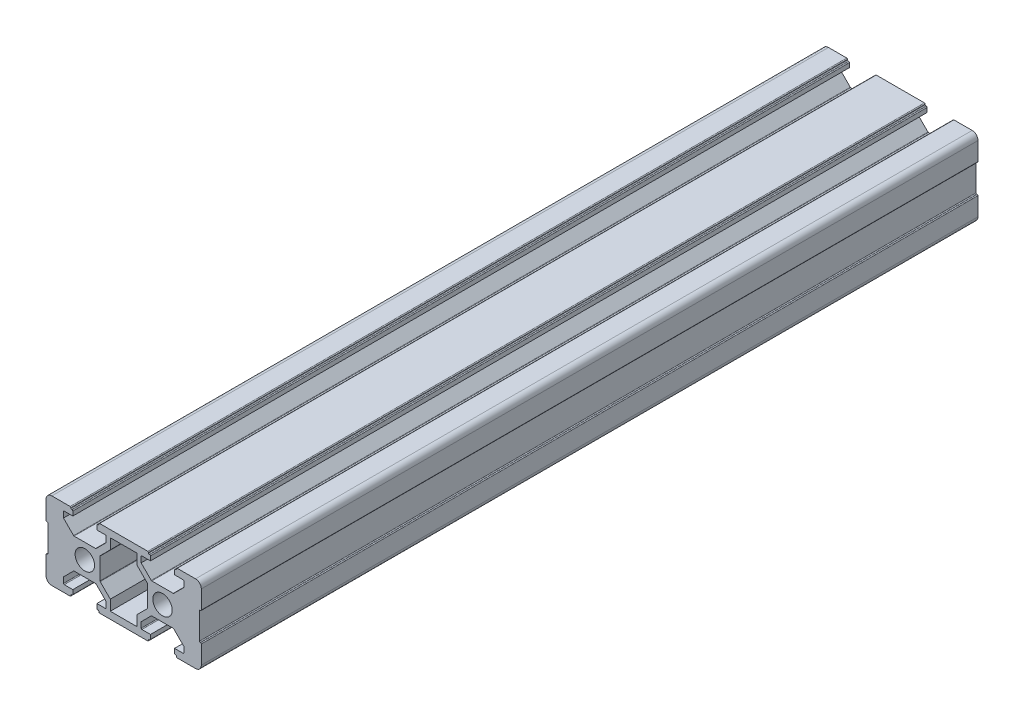
SolidWorks part; units mm, degrees
ref_plane "前视基准面" through (0, 0, 0) normal (0, 0, 1) x (1, 0, 0)
ref_plane "上视基准面" through (0, 0, 0) normal (0, 1, 0) x (1, 0, 0)
ref_plane "右视基准面" through (0, 0, 0) normal (1, 0, 0) x (0, 0, -1)
sketch "Sketch1" plane through (0, 0, 0) normal (0, 0, 1) x (1, 0, 0)
  line L0 (-8.5, 10) -> (-3.8, 10)
  line L3 (-8.5, -10) -> (-3.8, -10)
  line L5 (-10, 8.5) -> (-10, 3.8)
  line L6 (-2.7565, 3.9) -> (2.7565, 3.9)
  line L9 (-2.7565, -3.9) -> (2.7565, -3.9)
  line L10 (3.9, 2.7565) -> (3.9, -2.7565)
  line L13 (3.6, 9.7) -> (3.6, 9.8)
  line L14 (3.1, -8.2) -> (5.3, -8.2)
  line L15 (-2.8979, -3.9586) -> (-5.5, -6.5607)
  line L16 (-3.1, -8.2) -> (-3.1, -9.3)
  line L17 (3.1, -8.2) -> (3.1, -9.3)
  line L18 (-5.5, -6.5607) -> (-5.5, -8)
  line L19 (5.5, -6.5607) -> (5.5, -8)
  line L20 (-5.3, -8.2) -> (-3.1, -8.2)
  line L21 (-3.4, -9.5) -> (-3.3, -9.5)
  line L22 (3.8, -10) -> (8.5, -10)
  line L23 (3.3, -9.5) -> (3.4, -9.5)
  line L24 (-3.6, -9.7) -> (-3.6, -9.8)
  line L25 (3.6, -9.7) -> (3.6, -9.8)
  line L27 (-9.7, -3.6) -> (-9.8, -3.6)
  line L28 (-9.5, -3.4) -> (-9.5, -3.3)
  line L31 (-10, -3.8) -> (-10, -8.5)
  line L33 (3.8, 10) -> (8.5, 10)
  line L34 (2.8979, -3.9586) -> (5.5, -6.5607)
  line L40 (3.9586, -2.8979) -> (6.5607, -5.5)
  line L41 (3.3, 9.5) -> (3.4, 9.5)
  line L42 (30, 8.5) -> (30, 3.8)
  line L43 (3.1, 8.2) -> (3.1, 9.3)
  line L44 (3.1, 8.2) -> (5.3, 8.2)
  line L45 (5.5, 6.5607) -> (5.5, 8)
  line L46 (2.8979, 3.9586) -> (5.5, 6.5607)
  line L52 (3.9586, 2.8979) -> (6.5607, 5.5)
  line L53 (-3.6, 9.7) -> (-3.6, 9.8)
  line L54 (-3.4, 9.5) -> (-3.3, 9.5)
  line L55 (-3.1, 8.2) -> (-3.1, 9.3)
  line L56 (-5.3, 8.2) -> (-3.1, 8.2)
  line L57 (-5.5, 6.5607) -> (-5.5, 8)
  line L58 (-2.8979, 3.9586) -> (-5.5, 6.5607)
  line L59 (-9.5, 3.4) -> (-9.5, 3.3)
  line L60 (-9.7, 3.6) -> (-9.8, 3.6)
  line L65 (29.7, 3.6) -> (29.8, 3.6)
  line L66 (29.5, 3.4) -> (29.5, 3.3)
  line L76 (29.5, -3.4) -> (29.5, -3.3)
  line L77 (29.7, -3.6) -> (29.8, -3.6)
  line L78 (30, -3.8) -> (30, -8.5)
  line L79 (28.5, -10) -> (23.8, -10)
  line L80 (23.6, -9.7) -> (23.6, -9.8)
  line L81 (23.4, -9.5) -> (23.3, -9.5)
  line L82 (23.1, -8.2) -> (23.1, -9.3)
  line L83 (25.3, -8.2) -> (23.1, -8.2)
  line L84 (25.5, -6.5607) -> (25.5, -8)
  line L85 (22.8979, -3.9586) -> (25.5, -6.5607)
  line L86 (22.7565, -3.9) -> (17.2435, -3.9)
  line L87 (17.1021, -3.9586) -> (14.5, -6.5607)
  line L88 (14.5, -6.5607) -> (14.5, -8)
  line L89 (16.9, -8.2) -> (14.7, -8.2)
  line L90 (16.9, -8.2) -> (16.9, -9.3)
  line L91 (16.7, -9.5) -> (16.6, -9.5)
  line L92 (16.4, -9.7) -> (16.4, -9.8)
  line L93 (16.2, -10) -> (11.5, -10)
  line L94 (13.4393, 5.5) -> (13.4393, 8.2)
  line L96 (6.5607, 5.5) -> (6.5607, 8.2)
  line L97 (6.5607, 8.2) -> (13.4393, 8.2)
  line L99 (16.0414, -2.8979) -> (13.4393, -5.5)
  line L100 (16.1, 2.7565) -> (16.1, -2.7565)
  line L101 (16.0414, 2.8979) -> (13.4393, 5.5)
  line L107 (16.2, 10) -> (11.5, 10)
  line L108 (16.4, 9.7) -> (16.4, 9.8)
  line L109 (16.7, 9.5) -> (16.6, 9.5)
  line L110 (16.9, 8.2) -> (16.9, 9.3)
  line L111 (16.9, 8.2) -> (14.7, 8.2)
  line L112 (14.5, 6.5607) -> (14.5, 8)
  line L113 (17.1021, 3.9586) -> (14.5, 6.5607)
  line L114 (22.7565, 3.9) -> (17.2435, 3.9)
  line L115 (22.8979, 3.9586) -> (25.5, 6.5607)
  line L116 (25.5, 6.5607) -> (25.5, 8)
  line L117 (25.3, 8.2) -> (23.1, 8.2)
  line L118 (23.1, 8.2) -> (23.1, 9.3)
  line L119 (23.4, 9.5) -> (23.3, 9.5)
  line L120 (23.6, 9.7) -> (23.6, 9.8)
  line L121 (28.5, 10) -> (23.8, 10)
  line L122 (13.4393, -5.5) -> (13.4393, -8.2)
  line L124 (6.5607, -5.5) -> (6.5607, -8.2)
  line L125 (6.5607, -8.2) -> (13.4393, -8.2)
  line L127 (8.5, 10) -> (11.5, 10)
  line L128 (8.5, -10) -> (11.5, -10)
  line L129 (-9.5, -3.3) -> (-9.5, 3.3)
  line L130 (29.5, -3.3) -> (29.5, 3.3)
  arc A3 (-8.5, -10) -> (-10, -8.5) centre (-8.5, -8.5) cw
  arc A4 (-10, 8.5) -> (-8.5, 10) centre (-8.5, 8.5) cw
  arc A5 (3.4, -9.5) -> (3.6, -9.7) centre (3.4, -9.7) cw
  arc A6 (3.8, -10) -> (3.6, -9.8) centre (3.8, -9.8) cw
  arc A7 (3.3, -9.5) -> (3.1, -9.3) centre (3.3, -9.3) cw
  arc A8 (5.3, -8.2) -> (5.5, -8) centre (5.3, -8) ccw
  arc A11 (-2.7565, 3.9) -> (-2.8979, 3.9586) centre (-2.7565, 4.1) cw
  arc A12 (2.7565, 3.9) -> (2.8979, 3.9586) centre (2.7565, 4.1) ccw
  arc A13 (3.9586, 2.8979) -> (3.9, 2.7565) centre (4.1, 2.7565) ccw
  arc A14 (3.9, -2.7565) -> (3.9586, -2.8979) centre (4.1, -2.7565) ccw
  arc A15 (-2.8979, -3.9586) -> (-2.7565, -3.9) centre (-2.7565, -4.1) cw
  arc A16 (2.7565, -3.9) -> (2.8979, -3.9586) centre (2.7565, -4.1) cw
  arc A17 (-3.6, -9.8) -> (-3.8, -10) centre (-3.8, -9.8) cw
  arc A18 (-3.3, -9.5) -> (-3.1, -9.3) centre (-3.3, -9.3) ccw
  arc A19 (-3.6, -9.7) -> (-3.4, -9.5) centre (-3.4, -9.7) cw
  arc A24 (-5.3, -8.2) -> (-5.5, -8) centre (-5.3, -8) cw
  arc A31 (3.1, 9.3) -> (3.3, 9.5) centre (3.3, 9.3) cw
  arc A32 (3.6, 9.8) -> (3.8, 10) centre (3.8, 9.8) cw
  arc A33 (3.6, 9.7) -> (3.4, 9.5) centre (3.4, 9.7) cw
  arc A34 (-3.8, 10) -> (-3.6, 9.8) centre (-3.8, 9.8) cw
  arc A35 (-3.3, 9.5) -> (-3.1, 9.3) centre (-3.3, 9.3) cw
  arc A36 (-3.4, 9.5) -> (-3.6, 9.7) centre (-3.4, 9.7) cw
  arc A37 (5.5, 8) -> (5.3, 8.2) centre (5.3, 8) ccw
  arc A38 (-5.5, 8) -> (-5.3, 8.2) centre (-5.3, 8) cw
  arc A39 (-10, 3.8) -> (-9.8, 3.6) centre (-9.8, 3.8) ccw
  arc A41 (-9.7, 3.6) -> (-9.5, 3.4) centre (-9.7, 3.4) cw
  arc A42 (-10, -3.8) -> (-9.8, -3.6) centre (-9.8, -3.8) cw
  arc A44 (-9.5, -3.4) -> (-9.7, -3.6) centre (-9.7, -3.4) cw
  arc A45 (30, 8.5) -> (28.5, 10) centre (28.5, 8.5) ccw
  arc A46 (30, 3.8) -> (29.8, 3.6) centre (29.8, 3.8) cw
  arc A47 (29.7, 3.6) -> (29.5, 3.4) centre (29.7, 3.4) ccw
  arc A54 (29.5, -3.4) -> (29.7, -3.6) centre (29.7, -3.4) ccw
  arc A55 (30, -3.8) -> (29.8, -3.6) centre (29.8, -3.8) ccw
  arc A56 (28.5, -10) -> (30, -8.5) centre (28.5, -8.5) ccw
  arc A57 (23.6, -9.8) -> (23.8, -10) centre (23.8, -9.8) ccw
  arc A58 (23.6, -9.7) -> (23.4, -9.5) centre (23.4, -9.7) ccw
  arc A59 (23.3, -9.5) -> (23.1, -9.3) centre (23.3, -9.3) cw
  arc A60 (25.3, -8.2) -> (25.5, -8) centre (25.3, -8) ccw
  arc A61 (22.8979, -3.9586) -> (22.7565, -3.9) centre (22.7565, -4.1) ccw
  arc A62 (17.2435, -3.9) -> (17.1021, -3.9586) centre (17.2435, -4.1) ccw
  arc A63 (14.7, -8.2) -> (14.5, -8) centre (14.7, -8) cw
  arc A64 (16.7, -9.5) -> (16.9, -9.3) centre (16.7, -9.3) ccw
  arc A65 (16.6, -9.5) -> (16.4, -9.7) centre (16.6, -9.7) ccw
  arc A66 (16.2, -10) -> (16.4, -9.8) centre (16.2, -9.8) ccw
  arc A72 (16.1, -2.7565) -> (16.0414, -2.8979) centre (15.9, -2.7565) cw
  arc A73 (16.0414, 2.8979) -> (16.1, 2.7565) centre (15.9, 2.7565) cw
  arc A79 (16.4, 9.8) -> (16.2, 10) centre (16.2, 9.8) ccw
  arc A80 (16.4, 9.7) -> (16.6, 9.5) centre (16.6, 9.7) ccw
  arc A81 (16.9, 9.3) -> (16.7, 9.5) centre (16.7, 9.3) ccw
  arc A82 (14.5, 8) -> (14.7, 8.2) centre (14.7, 8) cw
  arc A83 (17.2435, 3.9) -> (17.1021, 3.9586) centre (17.2435, 4.1) cw
  arc A84 (22.7565, 3.9) -> (22.8979, 3.9586) centre (22.7565, 4.1) ccw
  arc A85 (25.5, 8) -> (25.3, 8.2) centre (25.3, 8) ccw
  arc A86 (23.3, 9.5) -> (23.1, 9.3) centre (23.3, 9.3) ccw
  arc A87 (23.4, 9.5) -> (23.6, 9.7) centre (23.4, 9.7) ccw
  arc A88 (23.8, 10) -> (23.6, 9.8) centre (23.8, 9.8) ccw
  point P11 (3.9, 3.9)
  point P19 (3.3697, 4.4303)
  point P20 (-10.6428, -10.6428)
  point P25 (-11.1731, -10.1124)
  point P26 (4.4303, 3.3697)
  point P28 (-10.1124, -11.1731)
  dimension "D3" = 0.2
  dimension "D4" = 0.2
  dimension "D5" = 0.2
  dimension "D9" = 0.2
  dimension "D6" = 1.8
  dimension "D7" = 0.5
extrude "Boss-Extrude1" add sketch "Sketch1" along normal blind 200
ref_plane "hole" through (0, 0, 200) normal (0, 0, 1) x (1, 0, 0)
sketch "Sketch2" plane through (0, 0, 200) normal (0, 0, 1) x (1, 0, 0)
  circle A0 centre (0, 0) radius 2.5
  circle A1 centre (20, 0) radius 2.5
  dimension "D1" = 5
extrude "Cut-Extrude1" cut sketch "Sketch2" against normal through all
sketch "Sketch3" plane through (0, -10, 0) normal (0, -1, 0) x (-1, 0, 0)
  line L0 (-3.8, -200) -> (-16.2, -200) construction
  line L1 (2.7565, -200) -> (-2.7565, -200) construction
  circle A0 centre (0, -183.3) radius 1.5
  circle A1 centre (0, -166.6) radius 1.5
  point P8 (0, -200)
  dimension "D1" = 16.7
  dimension "D2" = 16.7
  dimension "D3" = 0
  dimension "D4" = 0
  dimension "D5" = 3
  dimension "D6" = 3
extrude "Cut-Extrude2" cut sketch "Sketch3" against normal blind 42
sketch "Sketch4" plane through (0, -10, 0) normal (0, -1, 0) x (-1, 0, 0)
  line L0 (-17.2435, -200) -> (-22.7565, -200) construction
  line L1 (-3.8, -200) -> (-16.2, -200) construction
  circle A0 centre (-20, -166.6) radius 1.5
  circle A1 centre (-20, -183.3) radius 1.5
  point P6 (-20, -200)
  dimension "D1" = 0
  dimension "D2" = 0
  dimension "D3" = 16.7
  dimension "D4" = 16.7
  dimension "D5" = 3
  dimension "D6" = 3
extrude "Cut-Extrude3" cut sketch "Sketch4" against normal blind 22
